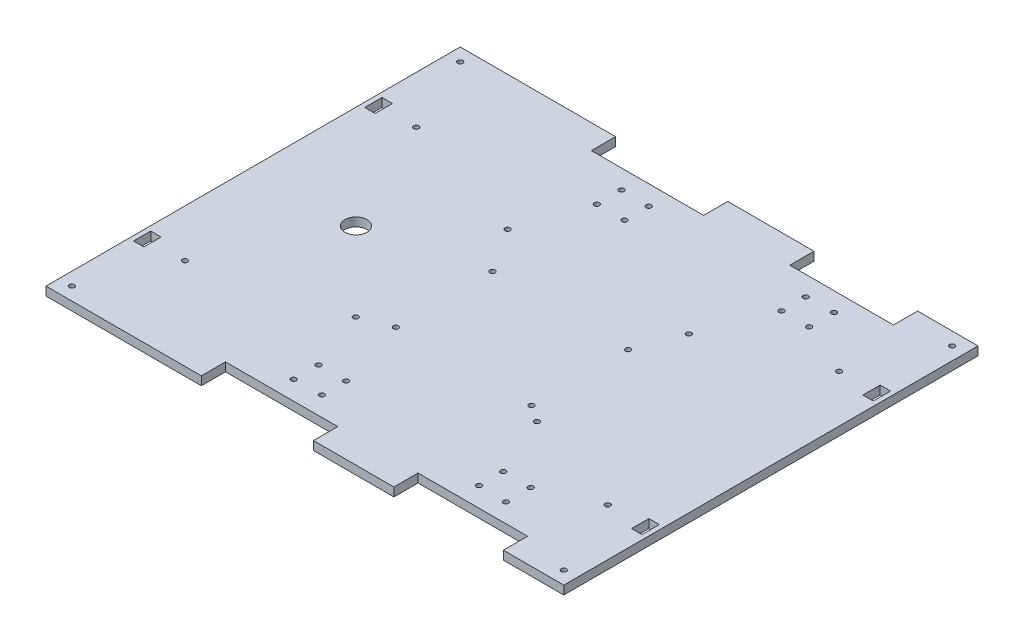
SolidWorks part; units mm, degrees
ref_plane "Front Plane" through (0, 0, 0) normal (0, 0, 1) x (1, 0, 0)
ref_plane "Top Plane" through (0, 0, 0) normal (0, 1, 0) x (1, 0, 0)
ref_plane "Right Plane" through (0, 0, 0) normal (1, 0, 0) x (0, 0, -1)
sketch "Sketch2" plane through (0, 0, 0) normal (0, 1, 0) x (1, 0, 0)
  line L1 (-150, -120) -> (150, -120)
  line L2 (-150, -120) -> (-150, 120)
  line L3 (-150, 120) -> (150, 120)
  line L4 (150, -120) -> (150, 120)
  line L5 (-150, -120) -> (150, 120) construction
  line L6 (-150, 120) -> (150, -120) construction
  point P0 (0, 0)
  dimension "D1" = 300
  dimension "D2" = 240
extrude "Boss-Extrude1" add sketch "Sketch2" along normal blind 5
sketch "Sketch3" plane through (0, 5, 0) normal (0, 1, 0) x (1, 0, 0)
  line L0 (150, -120) -> (150, 120) construction
  line L1 (150, 120) -> (-150, 120) construction
  circle A0 centre (142.5, 112.5) radius 1.5
  dimension "D1" = 3
  dimension "D3" = 7.5
  dimension "D2" = 7.5
extrude "Cut-Extrude1" cut sketch "Sketch3" against normal through all
mirror "Mirror1" about plane through (0, 0, 0) normal (1, 0, 0) of "Cut-Extrude1"
mirror "Mirror2" about plane through (0, 0, 0) normal (0, 0, 1) of "Mirror1", "Cut-Extrude1"
sketch "Sketch9" plane through (0, 0, 0) normal (0, -1, 0) x (-1, 0, 0)
  line L0 (0, 120) -> (0, -120) construction
  line L1 (150, -120) -> (-150, -120) construction
  line L2 (-150, 0) -> (150, 0) construction
  line L3 (150, 120) -> (150, -120) construction
  circle A0 centre (28, -39.25) radius 1.5
  point P6 (0, 0)
  point P12 (0, 0)
  dimension "D1" = 3
  dimension "D2" = 39.25
  dimension "D3" = 28
ref_plane "Plane10" through (-150, 5, -120) normal (-1, 0, 0) x (0, 0, 1)
sketch "Sketch16" plane through (-150, 5, -120) normal (-1, 0, 0) x (0, 0, 1)
sketch "Sketch17" plane through (0, 5, 0) normal (0, 1, 0) x (1, 0, 0)
  line L0 (-150, -120) -> (0, -120)
  line L2 (-150, -120) -> (150, -120) construction
ref_plane "Plane13" through (150, 5, 120) normal (0, 0, -1) x (-1, 0, 0)
sketch "Sketch19" plane through (0, 5, 0) normal (0, 1, 0) x (1, 0, 0)
sketch "Sketch23" plane through (0, 5, 0) normal (0, 1, 0) x (1, 0, 0)
  line L0 (-150, -120) -> (-150, -106)
  line L1 (-150, 120) -> (-150, -120) construction
  line L2 (-150, -106) -> (-60, -106)
  line L3 (5, -106) -> (-60, -106)
  line L5 (-60, -120) -> (5, -120)
  line L6 (-60, -120) -> (-60, -106)
  line L8 (5, -120) -> (5, -106)
  dimension "D1" = 65
  dimension "D2" = 90
extrude "Cut-Extrude16" cut sketch "Sketch23" against normal through all contours L3 L8 L5 L6
sketch "Sketch31" plane through (0, 5, 0) normal (0, 1, 0) x (1, 0, 0)
  line L0 (10, -106) -> (55, -106)
  line L1 (5, -120) -> (150, -120) construction
  line L2 (55, -106) -> (115, -106)
  line L3 (55, -106) -> (55, -120)
  line L4 (55, -120) -> (115, -120)
  line L5 (115, -106) -> (115, -120)
  dimension "D1" = 60
extrude "Cut-Extrude17" cut sketch "Sketch31" against normal blind 10
sketch "Sketch35" plane through (0, 5, 0) normal (0, 1, 0) x (1, 0, 0)
  line L0 (-2.6004, -106) -> (-2.6004, -1.764)
  line L1 (-50, -106) -> (10, -106) construction
  line L2 (-31.539, -48) -> (-31.539, -1.764)
  line L3 (-31.539, -1.764) -> (-31.539, -29.764)
  line L4 (-31.539, -1.764) -> (-44.789, -1.764)
  line L5 (-44.789, -1.764) -> (-44.789, -45.764)
  line L6 (-31.539, -29.764) -> (-31.539, 28.236)
  line L7 (-31.539, 28.236) -> (46.961, 28.236)
  line L8 (-31.539, -29.764) -> (46.961, -29.764)
  line L9 (-44.789, -45.764) -> (96.681, -45.764)
  circle A0 centre (-31.539, -29.764) radius 1.5
  circle A1 centre (-44.789, -45.764) radius 1.5
  circle A2 centre (46.961, -29.764) radius 1.5
  circle A4 centre (96.681, -45.764) radius 1.5
  dimension "D1" = 3
sketch "Sketch37" plane through (0, 5, 0) normal (0, 1, 0) x (1, 0, 0)
sketch "Sketch39" plane through (0, 0, 0) normal (0, -1, 0) x (1, 0, 0)
mirror "Mirror14" about plane through (0, 0, 0) normal (0, 0, 1) of "Cut-Extrude16"
sketch "Sketch45" plane through (0, 5, 0) normal (0, 1, 0) x (1, 0, 0)
  line L0 (-31.539, -29.764) -> (-31.539, 26.236)
  line L1 (-31.4891, 84.4844) -> (-31.4891, 106)
  line L2 (-50, 106) -> (10, 106) construction
  line L3 (-44.789, -45.764) -> (-44.789, 42.236)
  circle A0 centre (-31.539, 26.236) radius 1.5
  circle A1 centre (-44.789, 42.236) radius 1.5
sketch "Sketch47" plane through (0, 5, 0) normal (0, 1, 0) x (1, 0, 0)
  line L0 (-44.789, -45.764) -> (60.211, -45.764)
  circle A0 centre (60.211, -45.764) radius 1.5
  dimension "D1" = 3
sketch "Sketch48" plane through (0, 5, 0) normal (0, 1, 0) x (1, 0, 0)
  line L0 (60.211, -45.764) -> (60.211, 42.236)
  line L1 (60.211, 42.236) -> (-44.789, 42.236)
  circle A0 centre (60.211, 42.236) radius 1.5
extrude "Cut-Extrude29" cut sketch "Sketch45" against normal through all contours A1
extrude "Cut-Extrude30" cut sketch "Sketch47" against normal through all contours A0
extrude "Cut-Extrude31" cut sketch "Sketch48" against normal through all contours A0
extrude "Cut-Extrude32" cut sketch "Sketch35" against normal through all contours A1
extrude "Cut-Extrude33" cut sketch "Sketch9" against normal through all contours A0
sketch "Sketch52" plane through (0, 5, 0) normal (0, 1, 0) x (1, 0, 0)
  line L0 (-28, -39.25) -> (50.5, -39.25)
  line L1 (-28, -39.25) -> (-28, 16.75)
  line L2 (-28, 16.75) -> (50.5, 16.75)
  circle A0 centre (-28, 16.75) radius 1.5
  circle A1 centre (50.5, 16.75) radius 1.5
  circle A2 centre (50.5, -39.25) radius 1.5
extrude "Cut-Extrude34" cut sketch "Sketch52" against normal through all contours A0 | A1 | A2
mirror "Mirror20" about plane through (0, 0, 0) normal (0, 0, 1) of "Cut-Extrude17"
sketch "Sketch55" plane through (0, 5, 0) normal (0, 1, 0) x (1, 0, 0)
  line L0 (-31.5, -106) -> (-31.5, -95)
  line L1 (-31.5, -95) -> (-31.5, -84)
  line L2 (-31.5, -95) -> (-15.5, -94.6536)
  line L3 (-15.5, -94.6536) -> (-15.5, -80.6536)
  line L4 (-15.5, -80.6536) -> (-31.5, -80.6536)
  circle A0 centre (-31.5, -95) radius 1.5
  circle A6 centre (-15.5, -80.6536) radius 1.5
  circle A7 centre (-15.5, -94.6536) radius 1.5
  circle A8 centre (-31.5, -80.6536) radius 1.5
  dimension "D1" = 16
  dimension "D2" = 11
sketch "Sketch57" plane through (0, 5, 0) normal (0, 1, 0) x (1, 0, 0)
  line L0 (30, -120) -> (30, 120) construction
  line L3 (5, -120) -> (55, -120) construction
  line L4 (55, 120) -> (5, 120) construction
ref_plane "Plane16" through (30, 0, 0) normal (1, 0, 0) x (0, 0, -1)
sketch "Sketch10" plane through (0, 5, 0) normal (0, 1, 0) x (1, 0, 0)
  line L0 (-148, -59) -> (-116, -59) construction
  line L1 (-148, -59) -> (-148, -75) construction
  line L2 (-148, -75) -> (-116, -75) construction
  line L3 (-116, -75) -> (-116, -59) construction
  line L4 (-150, 120) -> (-150, -120) construction
  line L5 (-150, -120) -> (-60, -120) construction
  line L6 (-148, -67) -> (-116, -67) construction
  line L7 (-141.3, -72) -> (-147.3, -72)
  line L8 (-141.3, -72) -> (-141.3, -62)
  line L9 (-141.3, -62) -> (-147.3, -62)
  line L10 (-147.3, -72) -> (-147.3, -62)
  line L11 (-141.3, -72) -> (-147.3, -62) construction
  line L12 (-141.3, -62) -> (-147.3, -72) construction
  circle A0 centre (-122.5, -67) radius 1.5
  point P4 (-144.3, -67)
  dimension "D5" = 3
  dimension "D1" = 16
  dimension "D2" = 32
  dimension "D3" = 2
  dimension "D4" = 45
  dimension "D6" = 6.5
  dimension "D7" = 10
  dimension "D8" = 6
  dimension "D9" = 25.3
extrude "Cut-Extrude6" cut sketch "Sketch10" against normal through all
mirror "Mirror12" about plane through (0, 0, 0) normal (0, 0, 1) of "Cut-Extrude6"
mirror "Mirror13" about plane through (0, 0, 0) normal (1, 0, 0) of "Mirror12", "Cut-Extrude6"
sketch "Sketch58" plane through (0, 5, 0) normal (0, 1, 0) x (1, 0, 0)
  line L0 (142.5613, 112.4906) -> (142.4914, 112.4569)
  line L1 (96.4281, -139) -> (80.48, -139)
extrude "Cut-Extrude35" cut sketch "Sketch55" against normal through all contours A7 | A6 | A8 | A0
mirror "Mirror24" about plane through (30, 0, 0) normal (1, 0, 0) of "Cut-Extrude35"
mirror "Mirror25" about plane through (0, 0, 0) normal (0, 0, 1) of "Mirror24", "Cut-Extrude35"
sketch "Sketch59" plane through (0, 5, 0) normal (0, 1, 0) x (1, 0, 0)
  line L0 (51.5692, -120) -> (51.5692, -106)
  line L1 (5, -120) -> (55, -120) construction
  line L2 (51.5692, -106) -> (55, -106)
  line L3 (51.5692, -120) -> (55, -120)
  line L4 (55, -120) -> (55, -106)
extrude "Cut-Extrude37" cut sketch "Sketch59" against normal through all
sketch "Sketch60" plane through (0, 5, 0) normal (0, 1, 0) x (1, 0, 0)
  line L0 (-150.3539, 1.5714) -> (-90.4122, 0)
  circle A0 centre (-90.4122, 0) radius 6.38
extrude "Cut-Extrude38" cut sketch "Sketch60" against normal through all
